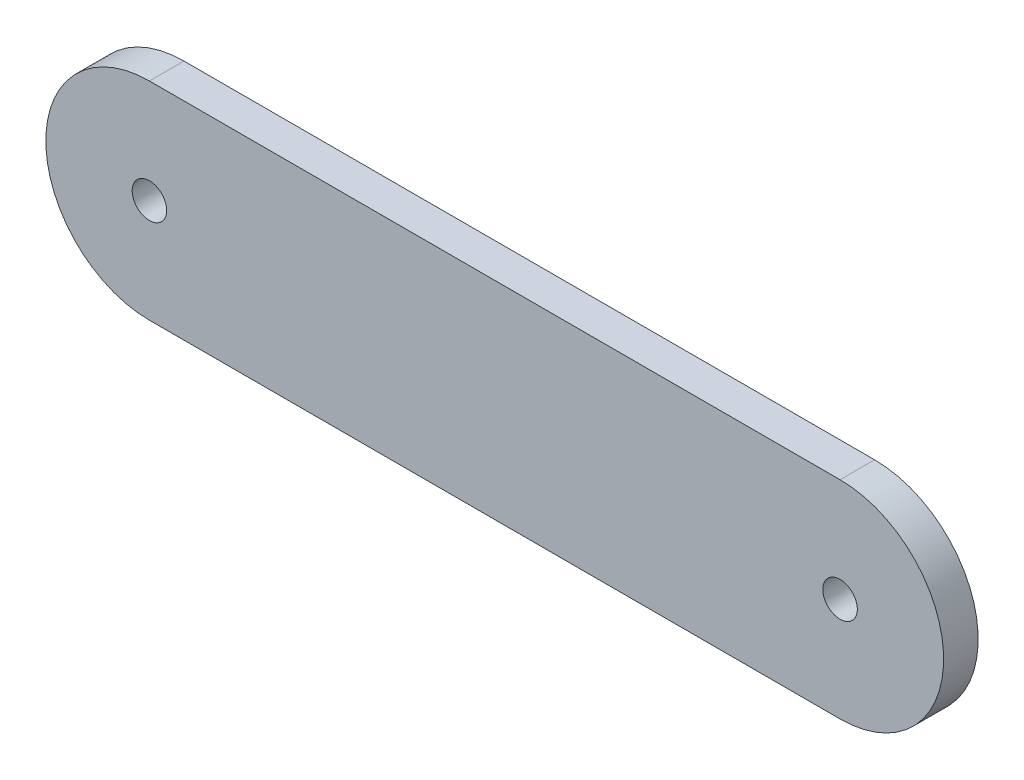
SolidWorks part; units mm, degrees
ref_plane "前视基准面" through (0, 0, 0) normal (0, 0, 1) x (1, 0, 0)
ref_plane "上视基准面" through (0, 0, 0) normal (0, 1, 0) x (1, 0, 0)
ref_plane "右视基准面" through (0, 0, 0) normal (1, 0, 0) x (0, 0, -1)
other "Configuration Table"
sketch "草图1" plane through (0, 0, 0) normal (0, 0, 1) x (1, 0, 0)
  line L0 (0, 0) -> (100, 0) construction
  line L1 (0, 15) -> (100, 15)
  line L2 (0, -15) -> (100, -15)
  arc A0 (0, 15) -> (0, -15) centre (0, 0) ccw
  arc A1 (100, -15) -> (100, 15) centre (100, 0) ccw
  point P3 (50, 0)
  dimension "D1" = 100
  dimension "D2" = 15
extrude "凸台-拉伸1" add sketch "草图1" along normal blind 5
sketch "草图2" plane through (0, 0, 0) normal (0, 0, -1) x (-1, 0, 0)
  line L2 (0, 15) -> (-100, 15)
  line L3 (-100, -15) -> (0, -15)
  line L4 (0, 15) -> (-100, 15)
  line L5 (-100, -15) -> (0, -15)
  circle A0 centre (0, 0) radius 2.5
  circle A1 centre (-100, 0) radius 2.5
  arc A2 (0, -15) -> (0, 15) centre (0, 0) ccw
  arc A3 (-100, 15) -> (-100, -15) centre (-100, 0) ccw
  arc A4 (0, -15) -> (0, 15) centre (0, 0) ccw
  arc A5 (-100, 15) -> (-100, -15) centre (-100, 0) ccw
  dimension "D2" = 5
  dimension "D3" = 5
  dimension "D1" = 0
extrude "切除-拉伸1" cut sketch "草图2" against normal through all contours A0 | A1
